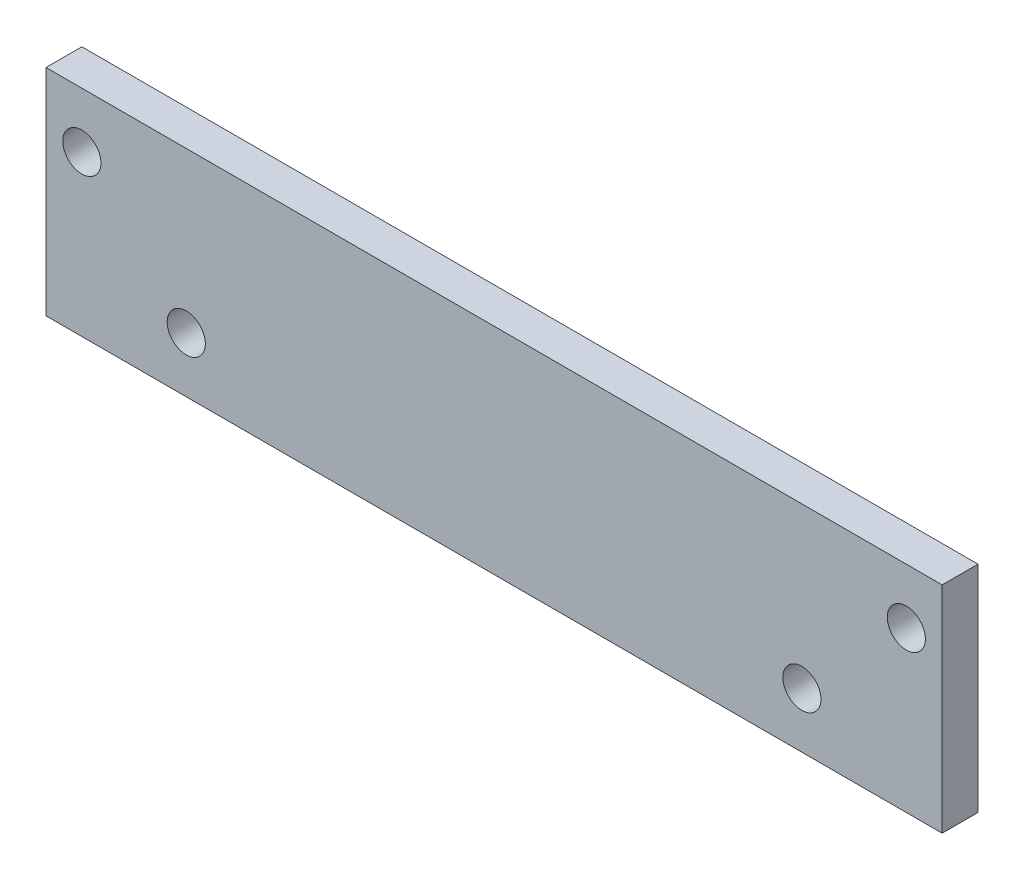
SolidWorks part; units mm, degrees
ref_plane "Front" through (0, 0, 0) normal (0, 0, 1) x (1, 0, 0)
ref_plane "Top" through (0, 0, 0) normal (0, 1, 0) x (1, 0, 0)
ref_plane "Right" through (0, 0, 0) normal (1, 0, 0) x (0, 0, -1)
sketch "Sketch1" plane through (0, 0, 0) normal (0, 0, 1) x (1, 0, 0)
  line L1 (-79.375, -19.05) -> (79.375, -19.05)
  line L2 (-79.375, -19.05) -> (-79.375, 19.05)
  line L3 (-79.375, 19.05) -> (79.375, 19.05)
  line L4 (79.375, -19.05) -> (79.375, 19.05)
  line L5 (-79.375, -19.05) -> (79.375, 19.05) construction
  line L6 (-79.375, 19.05) -> (79.375, -19.05) construction
  point P0 (0, 0)
  dimension "D1" = 158.75
  dimension "D2" = 38.1
extrude "Boss-Extrude1" add sketch "Sketch1" along normal blind 6.35
sketch "Sketch2" plane through (0, 0, 6.35) normal (0, 0, 1) x (1, 0, 0)
  line L0 (-73.025, 19.05) -> (-73.025, 9.2497) construction
  line L1 (79.375, 19.05) -> (-79.375, 19.05) construction
  line L2 (-73.025, 9.2497) -> (-54.5257, -9.2497) construction
  line L3 (-54.5257, -9.2497) -> (-54.5257, -19.05) construction
  line L4 (-79.375, -19.05) -> (79.375, -19.05) construction
  line L5 (-79.375, 19.05) -> (-79.375, -19.05) construction
  dimension "D1" = 135
  dimension "D2" = 26.162
  dimension "D3" = 6.35
hole_wizard "1/4 Clearance Hole1" positions "Sketch4" profile "Sketch3" hole size "1/4" standard "ANSI Inch" end condition through all
sketch "Sketch4" plane through (0, 0, 6.35) normal (0, 0, 1) x (1, 0, 0)
  point P0 (-73.025, 9.2497)
  point P3 (-54.5257, -9.2497)
sketch "Sketch3" plane through (-73.025, 9.2497, 6.35) normal (1, 0, 0) x (0, -1, 0)
  line L0 (0, 0) -> (0, 6.35)
  line L1 (0, 6.35) -> (3.3782, 6.35)
  line L2 (3.3782, 6.35) -> (3.3782, 0)
  line L5 (3.3782, 0) -> (0, 0)
  line L11 (0, -6.35) -> (0, 107.95) construction
  dimension "Thru Hole Dia." = 6.7564
  dimension "Thru Hole Depth" = 6.35
mirror "Mirror1" about plane through (0, 0, 0) normal (1, 0, 0) of "1/4 Clearance Hole1"
